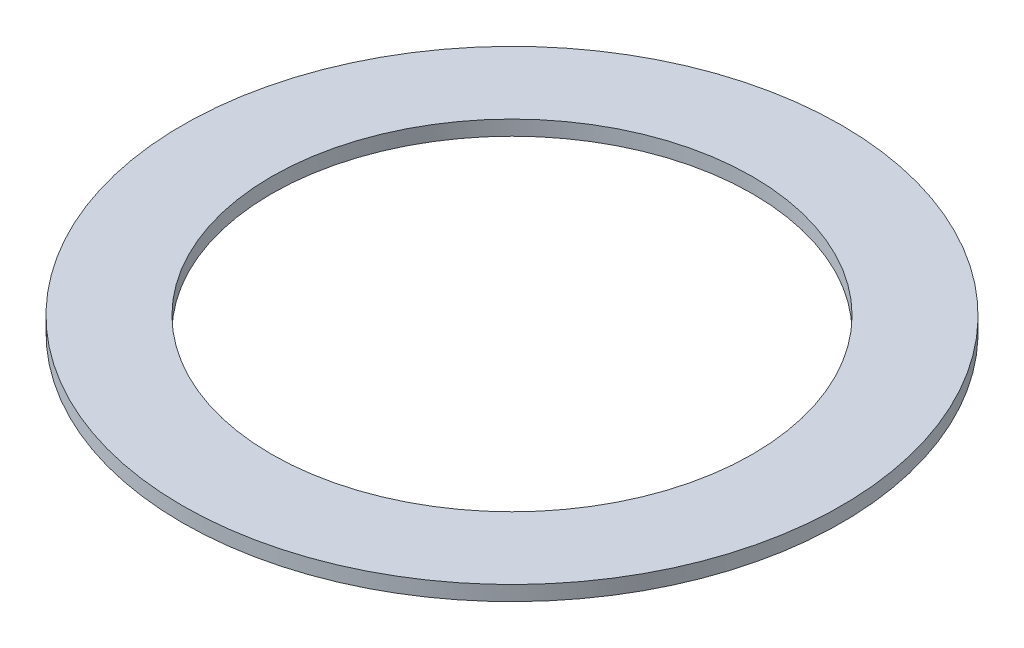
SolidWorks part; units mm, degrees
ref_plane "Front Plane" through (0, 0, 0) normal (0, 0, 1) x (1, 0, 0)
ref_plane "Top Plane" through (0, 0, 0) normal (0, 1, 0) x (1, 0, 0)
ref_plane "Right Plane" through (0, 0, 0) normal (1, 0, 0) x (0, 0, -1)
sketch "Sketch1" plane through (0, 0, 0) normal (0, 1, 0) x (1, 0, 0)
  circle A0 centre (0, 0) radius 8.1
  circle A1 centre (0, 0) radius 11.1
  dimension "D1" = 16.2
  dimension "D2" = 22.2
extrude "Boss-Extrude1" add sketch "Sketch1" along normal blind 0.5
